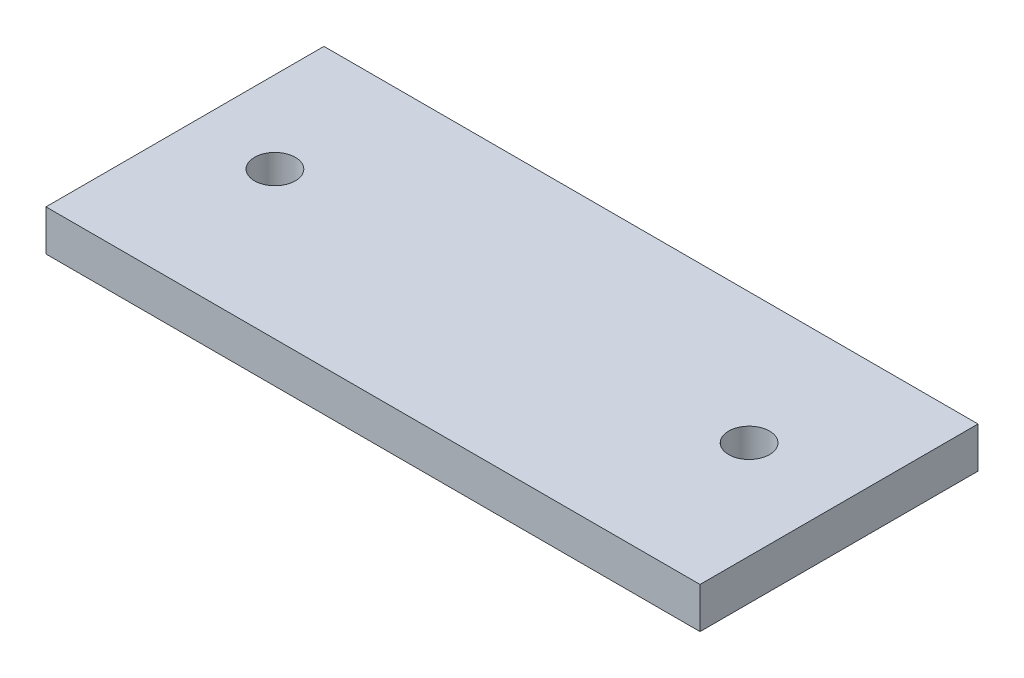
SolidWorks part; units mm, degrees
ref_plane "Front Plane" through (0, 0, 0) normal (0, 0, 1) x (1, 0, 0)
ref_plane "Top Plane" through (0, 0, 0) normal (0, 1, 0) x (1, 0, 0)
ref_plane "Right Plane" through (0, 0, 0) normal (1, 0, 0) x (0, 0, -1)
sketch "Sketch1" plane through (0, 0, 0) normal (0, 1, 0) x (1, 0, 0)
  line L1 (-25.4, 10.795) -> (25.4, 10.795)
  line L2 (-25.4, 10.795) -> (-25.4, -10.795)
  line L3 (-25.4, -10.795) -> (25.4, -10.795)
  line L4 (25.4, 10.795) -> (25.4, -10.795)
  line L5 (-25.4, 10.795) -> (25.4, -10.795) construction
  line L6 (-25.4, -10.795) -> (25.4, 10.795) construction
  circle A0 centre (-19.05, 0.635) radius 1.5875
  circle A1 centre (17.78, 0.635) radius 1.5875
  point P0 (0, 0)
  dimension "D6" = 3.175
  dimension "D1" = 21.59
  dimension "D2" = 50.8
  dimension "D3" = 10.16
  dimension "D4" = 6.35
  dimension "D5" = 7.62
extrude "Boss-Extrude1" add sketch "Sketch1" along normal blind 3.175
